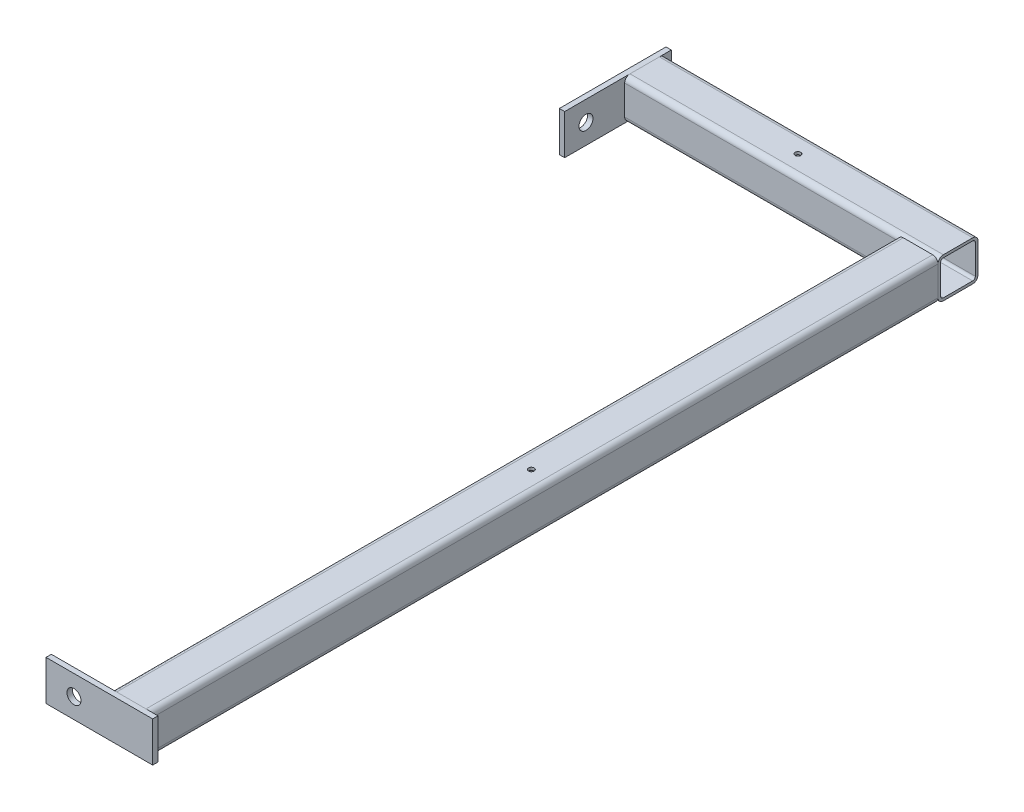
SolidWorks part; units mm, degrees
other "DetailItem1"
other "DetailItem3"
other "DetailItem4"
other "Weld Folder"
other "Weld Bead1"
other "Weld Bead3"
other "Weld Bead4"
material "AISI 304"
ref_plane "Front Plane" through (0, 0, 0) normal (0, 0, 1) x (1, 0, 0)
ref_plane "Top Plane" through (0, 0, 0) normal (0, 1, 0) x (1, 0, 0)
ref_plane "Right Plane" through (0, 0, 0) normal (1, 0, 0) x (0, 0, -1)
sketch3d "3DSketch1"
  line L1 (220, 0, 0) -> (220, 0, 605)
  line L12 (0, 0, 60) -> (0, 0, -20)
  line L13 (0, 0, 0) -> (220, 0, 0)
  line L14 (160, 0, 605) -> (240, 0, 605)
  dimension "D1" = 20
  dimension "D6" = 605
  dimension "D2" = 220
  dimension "D3" = 20
  dimension "D4" = 80
  dimension "D5" = 80
other "Square tube - configured 30 X 30 X 2"
ref_plane "Plane1" through (0, 0, 0) normal (1, 0, 0) x (0, 0, -1)
sketch "Sketch1" plane through (0, 0, 0) normal (1, 0, 0) x (0, 0, -1)
  line L0 (-11, -13) -> (11, -13)
  line L1 (-13, -11) -> (-13, 11)
  line L2 (11, 13) -> (-11, 13)
  line L3 (13, 11) -> (13, -11)
  line L4 (-11, -15) -> (11, -15)
  line L5 (-15, -11) -> (-15, 11)
  line L6 (11, 15) -> (-11, 15)
  line L7 (15, 11) -> (15, -11)
  arc A0 (15, 11) -> (11, 15) centre (11, 11) ccw
  arc A1 (11, -15) -> (15, -11) centre (11, -11) ccw
  arc A2 (-15, -11) -> (-11, -15) centre (-11, -11) ccw
  arc A3 (-11, 15) -> (-15, 11) centre (-11, 11) ccw
  arc A4 (-11, 13) -> (-13, 11) centre (-11, 11) ccw
  arc A5 (13, 11) -> (11, 13) centre (11, 11) ccw
  arc A6 (11, -13) -> (13, -11) centre (11, -11) ccw
  arc A7 (-13, -11) -> (-11, -13) centre (-11, -11) ccw
  point P0 (-15, 0)
  point P1 (15, 0)
  point P2 (0, 15)
  point P3 (0, -15)
  point P4 (0, 0)
  point P5 (-15, -15)
  point P6 (15, -15)
  point P7 (15, 15)
  point P8 (-15, 15)
  point P33 (0, 0)
  dimension "D1" = 4
  dimension "Thickness" = 2
  dimension "V_leg" = 30
other "Metal bar 30 X 4"
ref_plane "Plane2" through (0, 0, 60) normal (0, 0, -1) x (1, 0, 0)
sketch "Sketch11" plane through (0, 0, 60) normal (0, 0, -1) x (1, 0, 0)
  line L9 (0, -15) -> (-4, -15)
  line L10 (0, -15) -> (0, 15)
  line L11 (0, 15) -> (-4, 15)
  line L12 (-4, -15) -> (-4, 15)
  line L13 (0, -15) -> (-4, 15) construction
  line L14 (0, 15) -> (-4, -15) construction
  point P1 (10, 0)
  point P2 (0, 10)
  point P3 (0, -10)
  point P4 (0, 0)
  point P33 (0, 0)
  point P35 (-2, 0)
  dimension "thickness" = 4
  dimension "D3" = 2
  dimension "width" = 30
other "Metal bar 30 X 4(2)"
ref_plane "Plane3" through (160, 0, 605) normal (1, 0, 0) x (0, 0, -1)
sketch "Sketch14" plane through (160, 0, 605) normal (1, 0, 0) x (0, 0, -1)
  line L9 (0, -15) -> (-4, -15)
  line L10 (0, -15) -> (0, 15)
  line L11 (0, 15) -> (-4, 15)
  line L12 (-4, -15) -> (-4, 15)
  line L13 (0, -15) -> (-4, 15) construction
  line L14 (0, 15) -> (-4, -15) construction
  point P4 (0, 0)
  point P33 (0, 0)
  point P35 (-2, 0)
  dimension "width" = 30
  dimension "thickness" = 4
hole_wizard "Ø10.5 (10.5) Main Frame Mount Holes" positions "3DSketch2" profile "Sketch16" hole size "Ø10.5" standard "ANSI Metric"
sketch3d "3DSketch2"
  line L0 (-4, -15, -20) -> (-4, 15, -20) construction
  point P0 (-4, 0, 44)
  point P2 (181, 0, 609)
  point P21 (0, 0, 0)
  dimension "D1" = 64
  dimension "D2" = 59
sketch "Sketch16" plane through (-4, 0, 44) normal (0, 1, 0) x (0, 0, 1)
  line L0 (0, 0) -> (0, 211)
  line L1 (0, 211) -> (5.25, 211)
  line L2 (5.25, 211) -> (5.25, 0)
  line L5 (5.25, 0) -> (0, 0)
  line L11 (0, -6.35) -> (0, 107.95) construction
  dimension "Thru Hole Dia." = 10.5
  dimension "Thru Hole Depth" = 211
hole_wizard "Ø4.2 (4.2) Table Mount Holes" positions "Sketch17" profile "Sketch18" hole size "Ø4.2" standard "ANSI Metric" end condition through all
sketch "Sketch17" plane through (0, 15, 0) normal (0, 1, 0) x (1, 0, 0)
  line L0 (235, 11) -> (235, -11) construction
  line L1 (231, -15) -> (209, -15) construction
  line L2 (235, 15) -> (0, 15) construction
  point P0 (115, 0)
  point P2 (220, -305)
  point P12 (220, -15)
  dimension "D1" = 120
  dimension "D2" = 320
sketch "Sketch18" plane through (115, 15, 0) normal (1, 0, 0) x (0, 0, 1)
  line L0 (0, 0) -> (0, 30)
  line L1 (0, 30) -> (2.1, 30)
  line L2 (2.1, 30) -> (2.1, 0)
  line L5 (2.1, 0) -> (0, 0)
  line L11 (0, -6.35) -> (0, 107.95) construction
  dimension "Thru Hole Dia." = 4.2
  dimension "Thru Hole Depth" = 30
equation "\"D3@Sketch11\" = \"thickness@Sketch11\" / 2"
